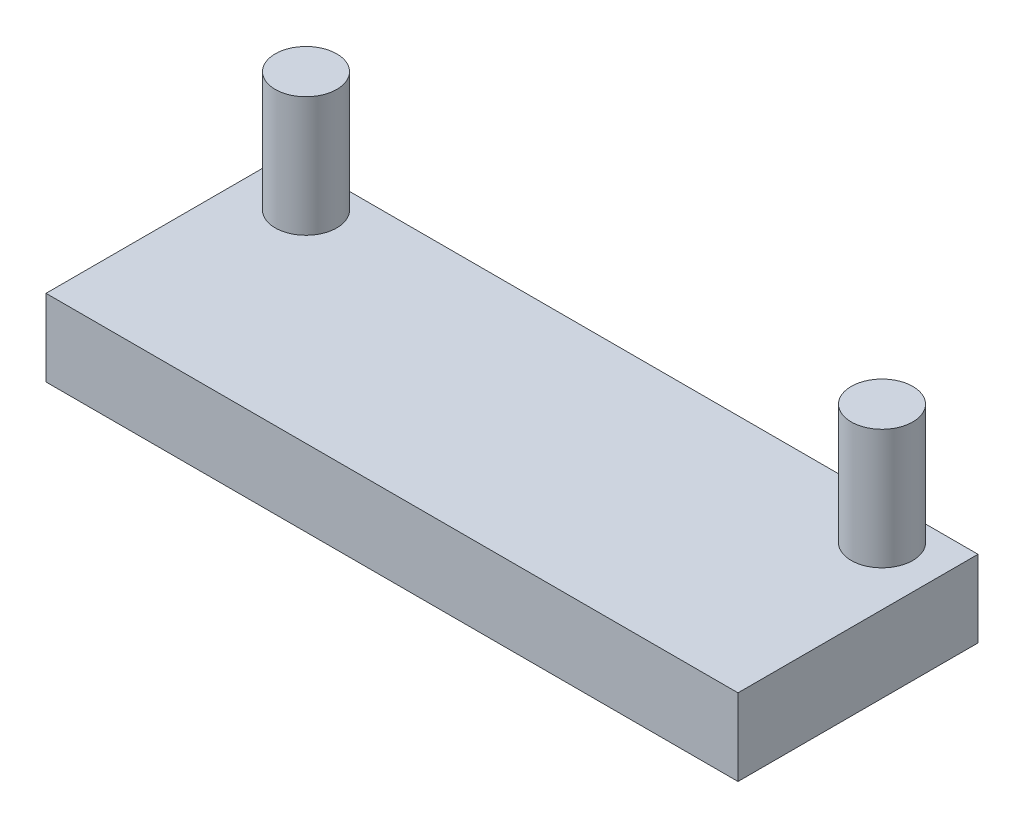
SolidWorks part; units mm, degrees
ref_plane "Front Plane" through (0, 0, 0) normal (0, 0, 1) x (1, 0, 0)
ref_plane "Top Plane" through (0, 0, 0) normal (0, 1, 0) x (1, 0, 0)
ref_plane "Right Plane" through (0, 0, 0) normal (1, 0, 0) x (0, 0, -1)
sketch "Sketch1" plane through (0, 0, 0) normal (0, 1, 0) x (1, 0, 0)
  line L0 (0, 0) -> (0, 8.733) construction
  line L1 (0, 0) -> (14.2084, 0) construction
  line L2 (-10.9855, 3.81) -> (-10.9855, -3.81)
  line L3 (-10.9855, -3.81) -> (10.9855, -3.81)
  line L4 (10.9855, -3.81) -> (10.9855, 3.81)
  line L5 (10.9855, 3.81) -> (-10.9855, 3.81)
  dimension "D1" = 21.971
  dimension "D2" = 7.62
extrude "Boss-Extrude1" add sketch "Sketch1" along normal blind 2.4384
sketch "Sketch2" plane through (0, 2.4384, 0) normal (0, 1, 0) x (1, 0, 0)
  line L0 (0, 0) -> (0, 3.81) construction
  line L1 (10.9855, 3.81) -> (-10.9855, 3.81) construction
  line L2 (0, 0) -> (10.9855, 0) construction
  line L3 (10.9855, -3.81) -> (10.9855, 3.81) construction
  circle A0 centre (-9.144, 2.6038) radius 0.9779
  circle A1 centre (9.144, 2.6038) radius 0.9779
  dimension "D1" = 1.9558
  dimension "D2" = 9.144
extrude "Boss-Extrude2" add sketch "Sketch2" along normal blind 3.81
